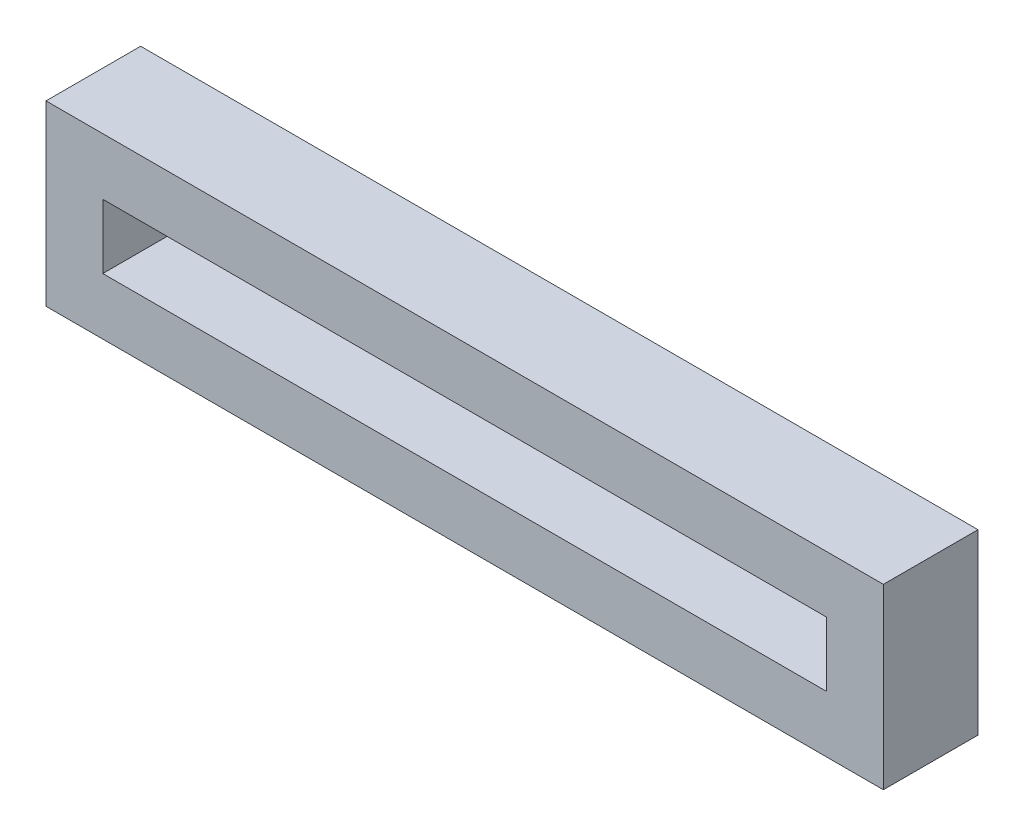
SolidWorks part; units mm, degrees
ref_plane "Front Plane" through (0, 0, 0) normal (0, 0, 1) x (1, 0, 0)
ref_plane "Top Plane" through (0, 0, 0) normal (0, 1, 0) x (1, 0, 0)
ref_plane "Right Plane" through (0, 0, 0) normal (1, 0, 0) x (0, 0, -1)
sketch "Sketch1" plane through (0, 0, 0) normal (0, 0, 1) x (1, 0, 0)
  line L0 (4.5022, 19.1002) -> (53.067, 19.1002)
  line L1 (0.6922, 10.9722) -> (56.877, 10.9722)
  line L2 (0.6922, 10.9722) -> (0.6922, 22.9102)
  line L3 (0.6922, 22.9102) -> (56.877, 22.9102)
  line L4 (56.877, 10.9722) -> (56.877, 22.9102)
  line L5 (53.067, 14.7822) -> (53.067, 19.1002)
  line L6 (4.5022, 14.7822) -> (53.067, 14.7822)
  line L7 (4.5022, 14.7822) -> (4.5022, 19.1002)
  dimension "D1" = 56.1848
  dimension "D2" = 11.938
  dimension "D3" = 3.81
extrude "Boss-Extrude1" add sketch "Sketch1" along normal blind 6.35
equation "\"D2@Sketch1\"=.5-.03"
